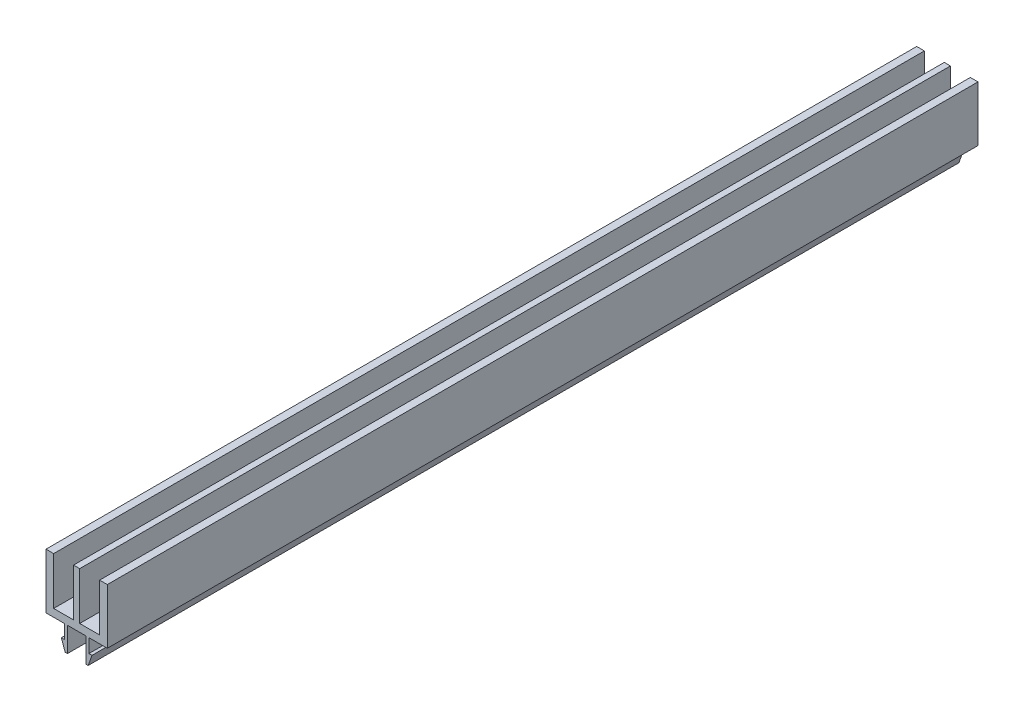
SolidWorks part; units mm, degrees
ref_plane "Plan de face" through (0, 0, 0) normal (0, 0, 1) x (1, 0, 0)
ref_plane "Plan de dessus" through (0, 0, 0) normal (0, 1, 0) x (1, 0, 0)
ref_plane "Plan de droite" through (0, 0, 0) normal (1, 0, 0) x (0, 0, -1)
ref_plane "Plan1" through (0, 0, 50) normal (0, 0, 1) x (1, 0, 0)
sketch "Esquisse1" plane through (0, 0, 50) normal (0, 0, 1) x (1, 0, 0)
  line L0 (-1, 2.5) -> (-7.5, 2.5)
  line L1 (-7.5, 2.5) -> (-7.5, 18)
  line L2 (-7.5, 18) -> (-10, 18)
  line L3 (-10, 18) -> (-10, 0)
  line L4 (-10, 0) -> (-4, 0)
  line L5 (-4, 0) -> (-4, -4.5)
  line L6 (-4, -4.5) -> (-5, -4.5)
  line L7 (-5, -4.5) -> (-3.75, -8)
  line L8 (-3.75, -8) -> (-3, -8)
  line L9 (-3, -8) -> (-3, 0)
  line L10 (-3, 0) -> (3, 0)
  line L11 (3, 0) -> (3, -8)
  line L12 (3, -8) -> (3.75, -8)
  line L13 (3.75, -8) -> (5, -4.5)
  line L14 (5, -4.5) -> (4, -4.5)
  line L15 (4, -4.5) -> (4, 0)
  line L16 (4, 0) -> (10, 0)
  line L17 (10, 0) -> (10, 18)
  line L18 (10, 18) -> (7.5, 18)
  line L19 (7.5, 18) -> (7.5, 2.5)
  line L20 (7.5, 2.5) -> (1, 2.5)
  line L21 (1, 2.5) -> (1, 18)
  line L22 (1, 18) -> (-1, 18)
  line L23 (-1, 18) -> (-1, 2.5)
extrude "Boss.-Extru.1" add sketch "Esquisse1" against normal blind 284
